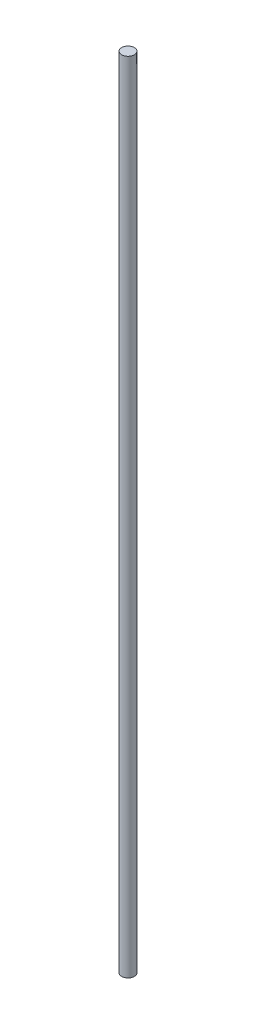
SolidWorks part; units mm, degrees
ref_plane "Front Plane" through (0, 0, 0) normal (0, 0, 1) x (1, 0, 0)
ref_plane "Top Plane" through (0, 0, 0) normal (0, 1, 0) x (1, 0, 0)
ref_plane "Right Plane" through (0, 0, 0) normal (1, 0, 0) x (0, 0, -1)
sketch "Sketch1" plane through (0, 0, 0) normal (0, 1, 0) x (1, 0, 0)
  circle A0 centre (0, 0) radius 4.7625
  dimension "D1" = 9.525
extrude "Boss-Extrude1" add sketch "Sketch1" along normal blind 603.25
